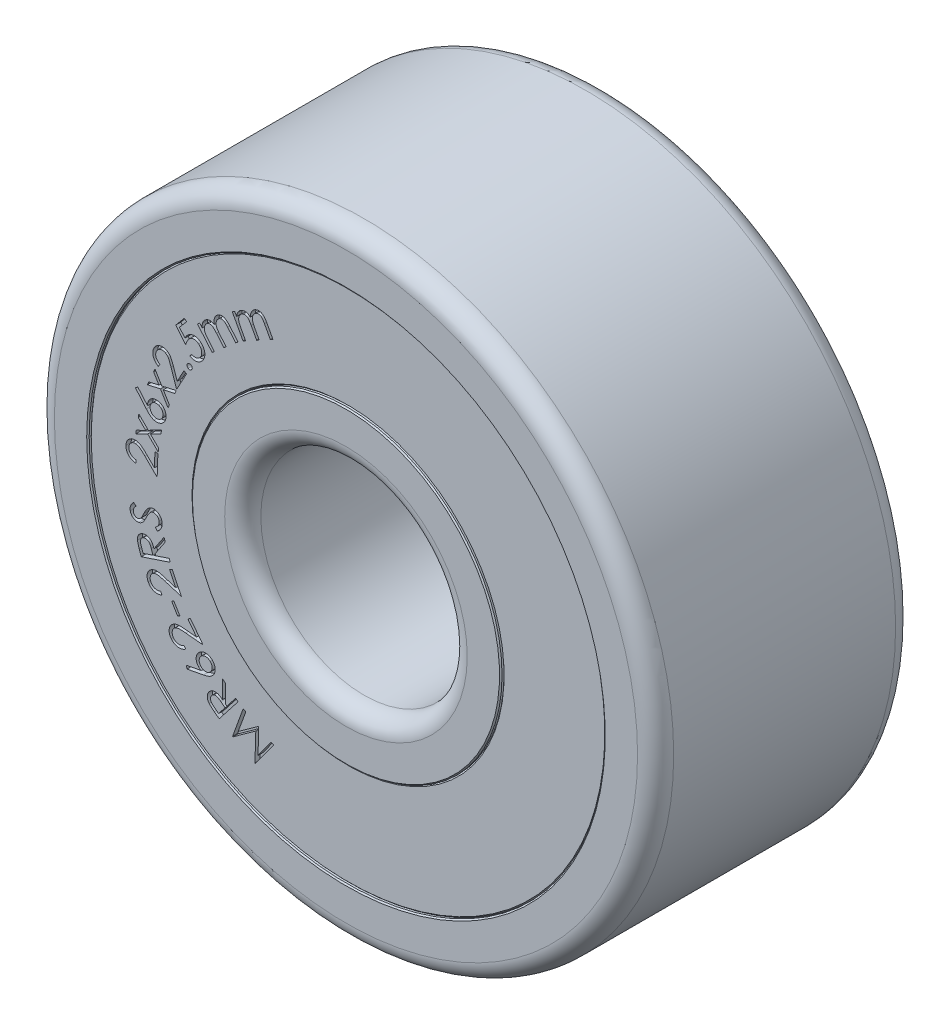
SolidWorks part; units mm, degrees
material "AISI 316 Annealed Stainless Steel Bar (SS)"
ref_plane "Front" through (0, 0, 0) normal (0, 0, 1) x (1, 0, 0)
ref_plane "Top" through (0, 0, 0) normal (0, 1, 0) x (1, 0, 0)
ref_plane "Right" through (0, 0, 0) normal (1, 0, 0) x (0, 0, -1)
sketch "LAYOUT R" plane through (0, 0, 0) normal (1, 0, 0) x (0, 0, -1)
  line L0 (-1.25, 1) -> (1.25, 1)
  line L1 (1.25, -3) -> (-1.25, -3) construction
  line L2 (1.25, -3) -> (1.25, 3) construction
  line L3 (1.25, 3) -> (-1.25, 3)
  line L4 (-1.25, -3) -> (-1.25, 3) construction
  line L5 (1.25, -3) -> (-1.25, 3) construction
  line L6 (1.25, 3) -> (-1.25, -3) construction
  line L7 (-1.25, 1.5) -> (1.25, 1.5)
  line L8 (-1.25, 2.5) -> (1.25, 2.5)
  line L11 (-17.5, 0) -> (17.5, 0) construction
  line L12 (-1.25, 3) -> (-1.25, 2.5)
  line L13 (1.25, 3) -> (1.25, 2.5)
  line L14 (-1.25, 2.5) -> (-1.25, 1.5)
  line L15 (1.25, 2.5) -> (1.25, 1.5)
  line L16 (-1.25, 1.5) -> (-1.25, 1)
  line L17 (1.25, 1.5) -> (1.25, 1)
  line L18 (-1.23, 2.5) -> (-1.23, 1.5)
  line L19 (1.23, 2.5) -> (1.23, 1.5)
  point P0 (0, 0)
  point P15 (0, 0)
  dimension "D1" = 2.5
  dimension "D2" = 6
  dimension "D3" = 1
  dimension "D6" = 0.02
  dimension "D7" = 0.02
  dimension "D4" = 1.5
  dimension "D5" = 2.5
sketch "Sketch R, INNER BODY" plane through (0, 0, 0) normal (1, 0, 0) x (0, 0, -1)
  line L0 (-1.25, 1) -> (1.25, 1) construction
  line L2 (-1.25, 1.5) -> (1.25, 1.5) construction
  line L4 (-1.25, 1) -> (1.25, 1)
  line L6 (-1.25, 1.5) -> (1.25, 1.5)
  line L8 (1.25, 1.5) -> (1.25, 1) construction
  line L9 (-1.25, 1.5) -> (-1.25, 1) construction
  line L10 (1.25, 1.5) -> (1.25, 1)
  line L11 (-1.25, 1.5) -> (-1.25, 1)
  line L12 (-17.5, 0) -> (17.5, 0) construction
  line L13 (-17.5, 0) -> (17.5, 0) construction
sketch "Sketch R, OUTER BODY" plane through (0, 0, 0) normal (1, 0, 0) x (0, 0, -1)
  line L2 (-1.25, 2.5) -> (1.25, 2.5) construction
  line L3 (1.25, 3) -> (-1.25, 3) construction
  line L6 (-1.25, 2.5) -> (1.25, 2.5)
  line L7 (1.25, 3) -> (-1.25, 3)
  line L8 (-17.5, 0) -> (17.5, 0) construction
  line L9 (-17.5, 0) -> (17.5, 0) construction
  line L10 (1.25, 3) -> (1.25, 2.5) construction
  line L11 (-1.25, 3) -> (-1.25, 2.5) construction
  line L12 (1.25, 3) -> (1.25, 2.5)
  line L13 (-1.25, 3) -> (-1.25, 2.5)
sketch "Sketch R, SEAL FACES" plane through (0, 0, 0) normal (1, 0, 0) x (0, 0, -1)
  line L0 (-17.5, 0) -> (17.5, 0) construction
  line L1 (-17.5, 0) -> (17.5, 0) construction
  line L3 (-1.25, 1.5) -> (1.25, 1.5) construction
  line L5 (-1.25, 2.5) -> (1.25, 2.5) construction
  line L7 (-1.23, 1.5) -> (1.23, 1.5)
  line L9 (-1.23, 2.5) -> (1.23, 2.5)
  line L10 (1.23, 2.5) -> (1.23, 1.5) construction
  line L11 (-1.23, 2.5) -> (-1.23, 1.5) construction
  line L12 (1.23, 2.5) -> (1.23, 1.5)
  line L13 (-1.23, 2.5) -> (-1.23, 1.5)
revolve "Revolve INNER BODY" add sketch "Sketch R, INNER BODY" angle 360 about L13
fillet "Fillet INNER BODY" radius 0.175 2 edges at (1, 0, 1.25) (1, 0, -1.25)
chamfer "Chamfer INNER BODY" distance 0.012 angle 45 2 edges at (1.5, 0, -1.25) (1.5, 0, 1.25)
revolve "Revolve OUTER BODY" add sketch "Sketch R, OUTER BODY" angle 360 about L9
fillet "Fillet OUTER BODY" radius 0.175 2 edges at (3, 0, -1.25) (3, 0, 1.25)
chamfer "Chamfer OUTER BODY" distance 0.012 angle 45 2 edges at (2.5, 0, 1.25) (2.5, 0, -1.25)
revolve "Revolve SEALS" add sketch "Sketch R, SEAL FACES" angle 360 about L1
chamfer "Chamfer SEALS" distance 0.012 angle 45 4 edges at (1.5, 0, -1.23) (2.5, 0, -1.23) (2.5, 0, 1.23) (1.5, 0, 1.23)
sketch "Sketch TEXT RADIUS 1 — MANUALLY ASSIGN TEXT AND FONT SIZE (FROM EQUATIONS)" plane through (0, 0, 1.23) normal (0, 0, 1) x (1, 0, 0)
  circle A0 centre (0, 0) radius 1.85 construction
  text T0 "MR62-2RS  2x6x2.5mm" font "Century Gothic" height 0.3
  dimension "D1" = 3.7
extrude "Cut-Extrude SEAL LABEL 1" cut sketch "Sketch TEXT RADIUS 1 — MANUALLY ASSIGN TEXT AND FONT SIZE (FROM EQUATIONS)" against normal blind 0.05
sketch "Sketch TEXT RADIUS 2 — MANUALLY ASSIGN TEXT AND FONT SIZE (FROM EQUATIONS)" plane through (0, 0, -1.23) normal (0, 0, -1) x (-1, 0, 0)
  circle A0 centre (0, 0) radius 1.85 construction
  text T0 "MR62-2RS  2x6x2.5mm" font "Century Gothic" height 0.3
  dimension "D1" = 3.7
extrude "Cut-Extrude SEAL LABEL 2" cut sketch "Sketch TEXT RADIUS 2 — MANUALLY ASSIGN TEXT AND FONT SIZE (FROM EQUATIONS)" against normal blind 0.05
equation "\"_i__BORE\"= 2"
equation "\"_i__OUTSIDE_DIAMETER\"= 6"
equation "\"_i__WIDTH\"= 2.5"
equation "\"_i_optional__TEXT_RADIUS_ADJUSTMENT\"= 0"
equation "\"_output__FONT_SIZE_mm\"= \"BODY_SPAN__SEAL__OF_RADIUS\" * \"param__FONT_SIZE_RATIO\"'MANUALLY ASSIGN TO FONT"
equation "\"BODY__HALF_WIDTH\"= \"_i__WIDTH\" / 2"
equation "\"BODY_SPAN___OF_DIAMETER\"= \"_i__OUTSIDE_DIAMETER\" - \"_i__BORE\""
equation "\"BODY_SPAN___OF_RADIUS\"= \"BODY_SPAN___OF_DIAMETER\" / 2"
equation "\"BODY_SPAN__BORE_AND_OD__OF RADIUS\"= ( \"BODY_SPAN___OF_RADIUS\" - \"BODY_SPAN__SEAL__OF_RADIUS\" ) / 2"
equation "\"BODY_SPAN__SEAL__OF_RADIUS\"= \"BODY_SPAN___OF_RADIUS\" * \"param__SEAL_PANEL_SPAN__RATIO_OF_BODY_RADIAN\""
equation "\"BORE__RADIUS\"= \"_i__BORE\" / 2"
equation "\"CORNER_RADII\"= \"_i__WIDTH\" * \"param__CORNER_RADII__ISO_MAX_RATIO_TO_WIDTH\""
equation "\"param__CORNER_RADII__ISO_MAX_RATIO_TO_WIDTH\"= 0.07'WHERE WIDTH IS LESS THAN DIAMETER"
equation "\"param__FONT_SIZE_RATIO\"= 0.3"
equation "\"param__SEAL_FACE_INSET__RATIO_OF_WIDTH\"= .01"
equation "\"param__SEAL_PANEL_SPAN__RATIO_OF_BODY_RADIAN\"= 0.5"
equation "\"param__SIDE_CHAMFERS__RATIO_TO_OD\"= 1 / 500"
equation "\"RING_INNER__OUTSIDE_RADIUS\"= \"BORE__RADIUS\" + \"BODY_SPAN__BORE_AND_OD__OF RADIUS\""
equation "\"RING_OUTER__OUTSIDE_RADIUS\"= ( \"_i__OUTSIDE_DIAMETER\" / 2 ) - \"BODY_SPAN__BORE_AND_OD__OF RADIUS\""
equation "\"SEAL_FACE_INSET\"= \"_i__WIDTH\" * \"param__SEAL_FACE_INSET__RATIO_OF_WIDTH\""
equation "\"SIDE_FACE_AND_SEAL_CHAMFERS\"= \"_i__OUTSIDE_DIAMETER\" * \"param__SIDE_CHAMFERS__RATIO_TO_OD\""
equation "\"TEXT_RADIUS\"= \"_i__BORE\" + ( \"BODY_SPAN___OF_DIAMETER\" / 2 ) - \"_output__FONT_SIZE_mm\" + \"_i_optional__TEXT_RADIUS_ADJUSTMENT\""
equation "\"D1@Chamfer INNER BODY\"=\"SIDE_FACE_AND_SEAL_CHAMFERS\""
equation "\"D1@Chamfer OUTER BODY\"=\"SIDE_FACE_AND_SEAL_CHAMFERS\""
equation "\"D1@Chamfer SEALS\"=\"SIDE_FACE_AND_SEAL_CHAMFERS\""
equation "\"D1@Fillet INNER BODY\"=\"CORNER_RADII\""
equation "\"D1@Fillet OUTER BODY\"=\"CORNER_RADII\""
equation "\"D1@LAYOUT R\"=\"_i__WIDTH\""
equation "\"D1@Sketch TEXT RADIUS 1 — MANUALLY ASSIGN TEXT AND FONT SIZE (FROM EQUATIONS)\" = \"TEXT_RADIUS\""
equation "\"D1@Sketch TEXT RADIUS 2 — MANUALLY ASSIGN TEXT AND FONT SIZE (FROM EQUATIONS)\" = \"TEXT_RADIUS\""
equation "\"D2@LAYOUT R\"=\"_i__OUTSIDE_DIAMETER\""
equation "\"D3@LAYOUT R\"=\"BORE__RADIUS\""
equation "\"D4@LAYOUT R\"=\"RING_INNER__OUTSIDE_RADIUS\""
equation "\"D5@LAYOUT R\"=\"RING_OUTER__OUTSIDE_RADIUS\""
